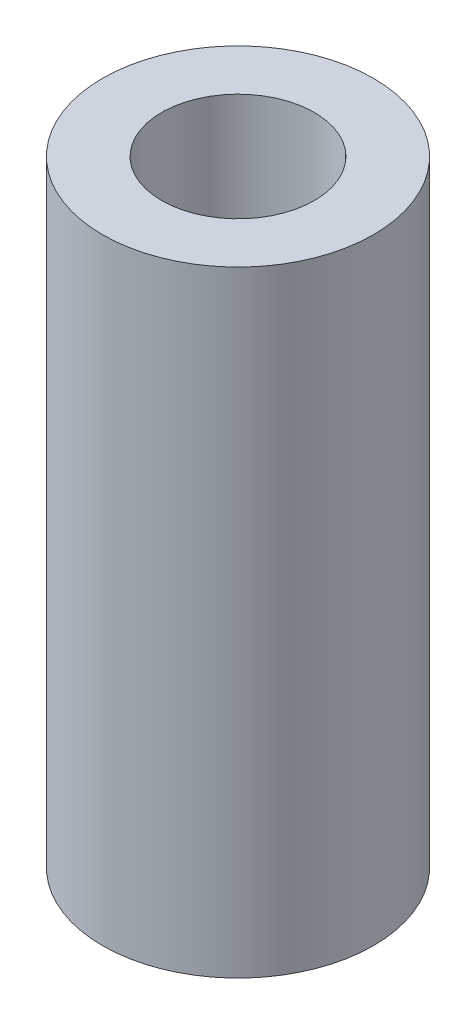
SolidWorks part; units mm, degrees
ref_plane "Front Plane" through (0, 0, 0) normal (0, 0, 1) x (1, 0, 0)
ref_plane "Top Plane" through (0, 0, 0) normal (0, 1, 0) x (1, 0, 0)
ref_plane "Right Plane" through (0, 0, 0) normal (1, 0, 0) x (0, 0, -1)
sketch "Sketch1" plane through (0, 0, 0) normal (0, 1, 0) x (1, 0, 0)
  circle A0 centre (0, 0) radius 1.55
  circle A1 centre (0, 0) radius 2.75
  dimension "D1" = 3.1
  dimension "D2" = 5.5
extrude "Boss-Extrude1" add sketch "Sketch1" along normal blind 12.5
